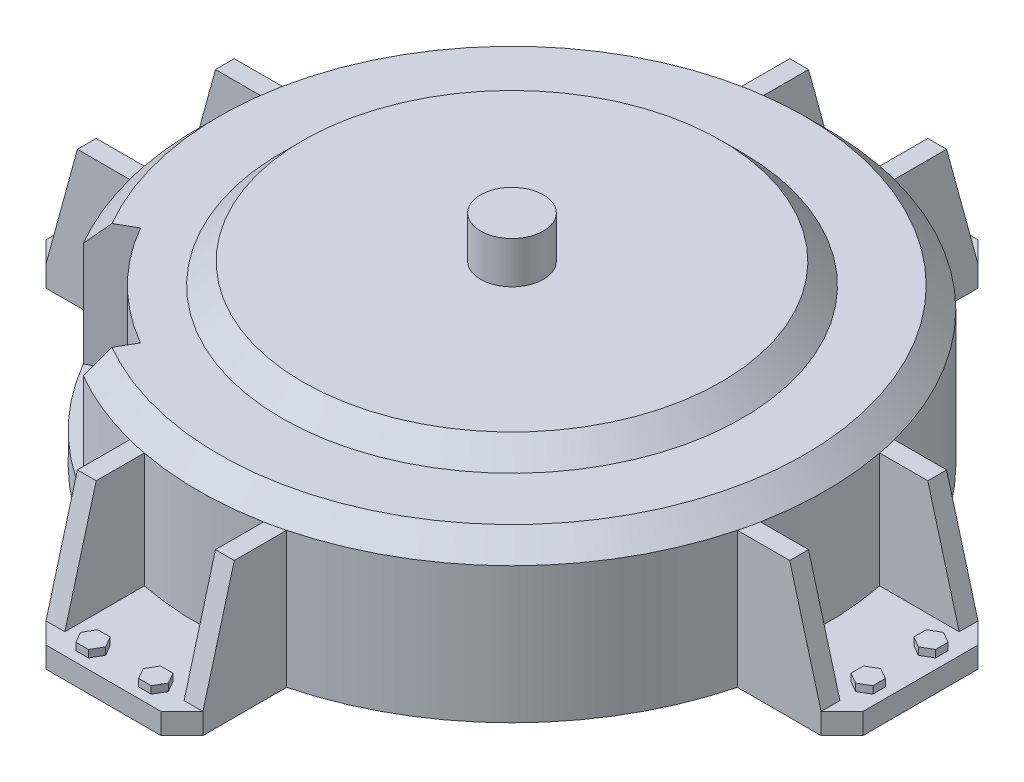
SolidWorks part; units mm, degrees
material "1023 Carbon Steel Sheet (SS)"
ref_plane "Front Plane" through (0, 0, 0) normal (0, 0, 1) x (1, 0, 0)
ref_plane "Top Plane" through (0, 0, 0) normal (0, 1, 0) x (1, 0, 0)
ref_plane "Right Plane" through (0, 0, 0) normal (1, 0, 0) x (0, 0, -1)
sketch "Sketch1" plane through (0, 0, 0) normal (0, 1, 0) x (1, 0, 0)
  line L0 (397.0477, 207.463) -> (631.0234, 207.463) construction
  circle A0 centre (0, 0) radius 150
  dimension "D1" = 300
extrude "Boss-Extrude1" add sketch "Sketch1" along normal blind 75
chamfer "Chamfer1" distance 10 angle 45 1 edges at (0, 75, 150)
sketch "Sketch2" plane through (0, 75, 0) normal (0, 1, 0) x (1, 0, 0)
  line L0 (0, 0) -> (-276.9019, 0) construction
  line L2 (-145.2369, 37.5) -> (-195.2369, 37.5)
  line L3 (-195.2369, 37.5) -> (-195.2369, -37.5)
  line L4 (-195.2369, -37.5) -> (-145.2369, -37.5)
  circle A0 centre (0, 0) radius 150 construction
  circle A2 centre (0, 0) radius 150
  arc A3 (-145.2369, 37.5) -> (-145.2369, -37.5) centre (0, 0) ccw
  dimension "D1" = 50
  dimension "D2" = 75
  dimension "D3" = 37.5
  dimension "D4" = 0
extrude "Boss-Extrude2" add sketch "Sketch2" along normal blind 10 from offset 75 offset against normal yes
chamfer "Chamfer2" distance 10 angle 45 1 edges at (-195.2369, 5, 37.5)
chamfer "Chamfer3" distance 10 angle 45 1 edges at (-195.2369, 5, -37.5)
sketch "Sketch3" plane through (0, 0, 37.5) normal (0, 0, 1) x (1, 0, 0)
  line L0 (-185.2369, 10) -> (-145.2369, 10)
  line L1 (-145.2369, 10) -> (-145.2369, 65)
  line L2 (-150, 65) -> (150, 65) construction
  line L3 (-145.2369, 65) -> (-170.2369, 65)
  line L4 (-170.2369, 65) -> (-185.2369, 10)
  dimension "D1" = 25
extrude "Boss-Extrude3" add sketch "Sketch3" against normal blind 9
sketch "Sketch4" plane through (0, 10, 0) normal (0, 1, 0) x (1, 0, 0)
  line L0 (-150, 0) -> (-238.0859, 0) construction
  line L1 (-185.2369, -28.5) -> (-185.2369, 46.3332) construction
  line L2 (-170.2369, -28.5) -> (-185.2369, -28.5) construction
  line L3 (-180.0407, -12) -> (-185.2369, -9)
  line L4 (-185.2369, -9) -> (-190.433, -12)
  line L5 (-190.433, -12) -> (-190.433, -18)
  line L6 (-190.433, -18) -> (-185.2369, -21)
  line L7 (-185.2369, -21) -> (-180.0407, -18)
  line L8 (-180.0407, -18) -> (-180.0407, -12)
  circle A0 centre (0, 0) radius 150 construction
  circle A1 centre (-185.2369, -15) radius 5.1962 construction
  dimension "D1" = 6
  dimension "D2" = 13.5
extrude "Boss-Extrude4" add sketch "Sketch4" along normal blind 3.5
mirror "Mirror1" about plane through (0, 0, 0) normal (0, 0, 1) of "Boss-Extrude3", "Boss-Extrude4"
pattern_circular "CirPattern1" count 4 over 360 about axis through (0, 0, 0) along (0, 1, 0) of "Mirror1", "Boss-Extrude4", "Boss-Extrude3", "Chamfer3", "Chamfer2", "Boss-Extrude2"
sketch "Sketch5" plane through (0, 75, 0) normal (0, 1, 0) x (1, 0, 0)
  line L0 (-130, 0) -> (0, 0) construction
  line L1 (0, -130) -> (0, 130) construction
  line L2 (-112.5833, -65) -> (-129.9038, -75)
  line L3 (-65, -112.5833) -> (-75, -129.9038)
  arc A0 (-112.5833, -65) -> (-65, -112.5833) centre (0, 0) ccw
  arc A17 (-147.2676, -28.5) -> (-145.2369, -37.5) centre (0, 0) ccw
  arc A18 (-145.2369, -37.5) -> (-37.5, -145.2369) centre (0, 0) ccw
  arc A19 (-37.5, -145.2369) -> (-28.5, -147.2676) centre (0, 0) ccw
  arc A20 (-28.5, -147.2676) -> (28.5, -147.2676) centre (0, 0) ccw
  arc A21 (28.5, -147.2676) -> (37.5, -145.2369) centre (0, 0) ccw
  arc A22 (37.5, -145.2369) -> (145.2369, -37.5) centre (0, 0) ccw
  arc A23 (145.2369, -37.5) -> (147.2676, -28.5) centre (0, 0) ccw
  arc A24 (147.2676, -28.5) -> (147.2676, 28.5) centre (0, 0) ccw
  arc A25 (147.2676, 28.5) -> (145.2369, 37.5) centre (0, 0) ccw
  arc A26 (145.2369, 37.5) -> (37.5, 145.2369) centre (0, 0) ccw
  arc A27 (37.5, 145.2369) -> (28.5, 147.2676) centre (0, 0) ccw
  arc A28 (28.5, 147.2676) -> (-28.5, 147.2676) centre (0, 0) ccw
  arc A29 (-28.5, 147.2676) -> (-37.5, 145.2369) centre (0, 0) ccw
  arc A30 (-37.5, 145.2369) -> (-145.2369, 37.5) centre (0, 0) ccw
  arc A31 (-145.2369, 37.5) -> (-147.2676, 28.5) centre (0, 0) ccw
  arc A32 (-147.2676, 28.5) -> (-147.2676, -28.5) centre (0, 0) ccw
  arc A34 (-129.9038, -75) -> (-75, -129.9038) centre (0, 0) ccw
  arc A39 (145.2369, -37.5) -> (147.2676, -28.5) centre (0, 0) ccw
  circle M22 centre (0, 0) radius 140
  dimension "D1" = 260
  dimension "D3" = 30
  dimension "D4" = 30
  dimension "D2" = 0
extrude "Cut-Extrude1" cut sketch "Sketch5" against normal blind 60 contours L2 A34 L3 M22 | A0 L2 L3 M22
sketch "Sketch7" plane through (0, 75, 0) normal (0, 1, 0) x (1, 0, 0)
  circle A0 centre (0, 0) radius 110
  dimension "D1" = 220
extrude "Boss-Extrude5" add sketch "Sketch7" along normal blind 10 draft 45
sketch "Sketch8" plane through (0, 85, 0) normal (0, 1, 0) x (1, 0, 0)
  circle A0 centre (0, 0) radius 15
  dimension "D1" = 30
extrude "Boss-Extrude6" add sketch "Sketch8" along normal blind 20
